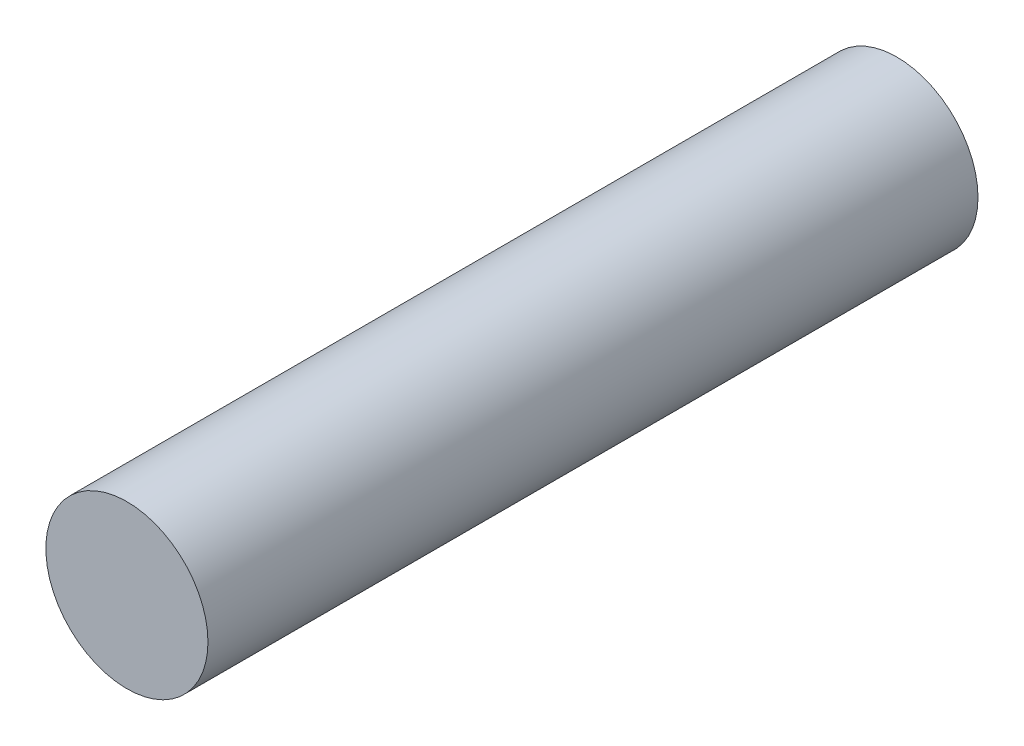
SolidWorks part; units mm, degrees
ref_plane "Front Plane" through (0, 0, 0) normal (0, 0, 1) x (1, 0, 0)
ref_plane "Top Plane" through (0, 0, 0) normal (0, 1, 0) x (1, 0, 0)
ref_plane "Right Plane" through (0, 0, 0) normal (1, 0, 0) x (0, 0, -1)
sketch "Sketch1" plane through (0, 0, 0) normal (0, 0, 1) x (1, 0, 0)
  circle A0 centre (0, 0) radius 10
extrude "Boss-Extrude1" add sketch "Sketch1" along normal blind 95
